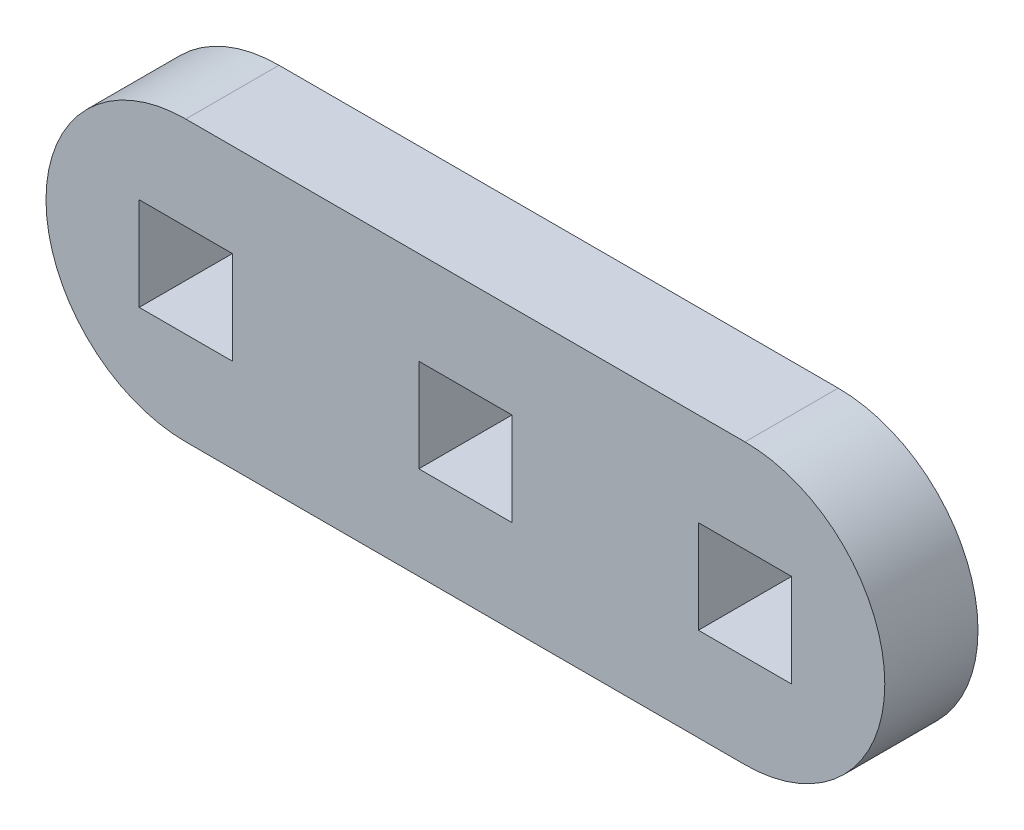
SolidWorks part; units mm, degrees
ref_plane "Alzado" through (0, 0, 0) normal (0, 0, 1) x (1, 0, 0)
ref_plane "Planta" through (0, 0, 0) normal (0, 1, 0) x (1, 0, 0)
ref_plane "Vista lateral" through (0, 0, 0) normal (1, 0, 0) x (0, 0, -1)
sketch "Model" plane through (0, 0, 0) normal (0, 0, 1) x (1, 0, 0)
  line L0 (10.9374, 296.5453) -> (10.9374, 293.5453)
  line L1 (13.9374, 296.5453) -> (10.9374, 296.5453)
  line L2 (13.9374, 293.5453) -> (13.9374, 296.5453)
  line L3 (10.9374, 293.5453) -> (13.9374, 293.5453)
  line L4 (19.9374, 296.5453) -> (19.9374, 293.5453)
  line L5 (22.9374, 296.5453) -> (19.9374, 296.5453)
  line L6 (22.9374, 293.5453) -> (22.9374, 296.5453)
  line L7 (19.9374, 293.5453) -> (22.9374, 293.5453)
  line L8 (28.9374, 296.5453) -> (28.9374, 293.5453)
  line L9 (31.9374, 296.5453) -> (28.9374, 296.5453)
  line L10 (31.9374, 293.5453) -> (31.9374, 296.5453)
  line L11 (28.9374, 293.5453) -> (31.9374, 293.5453)
  line L12 (12.4374, 299.5453) -> (30.4374, 299.5453)
  line L13 (12.4374, 290.5453) -> (30.4374, 290.5453)
  arc A0 (12.4374, 299.5453) -> (12.4374, 290.5453) centre (12.4374, 295.0453) ccw
  arc A1 (30.4374, 290.5453) -> (30.4374, 299.5453) centre (30.4374, 295.0453) ccw
extrude "Saliente-Extruir1" add sketch "Model" along normal blind 3
